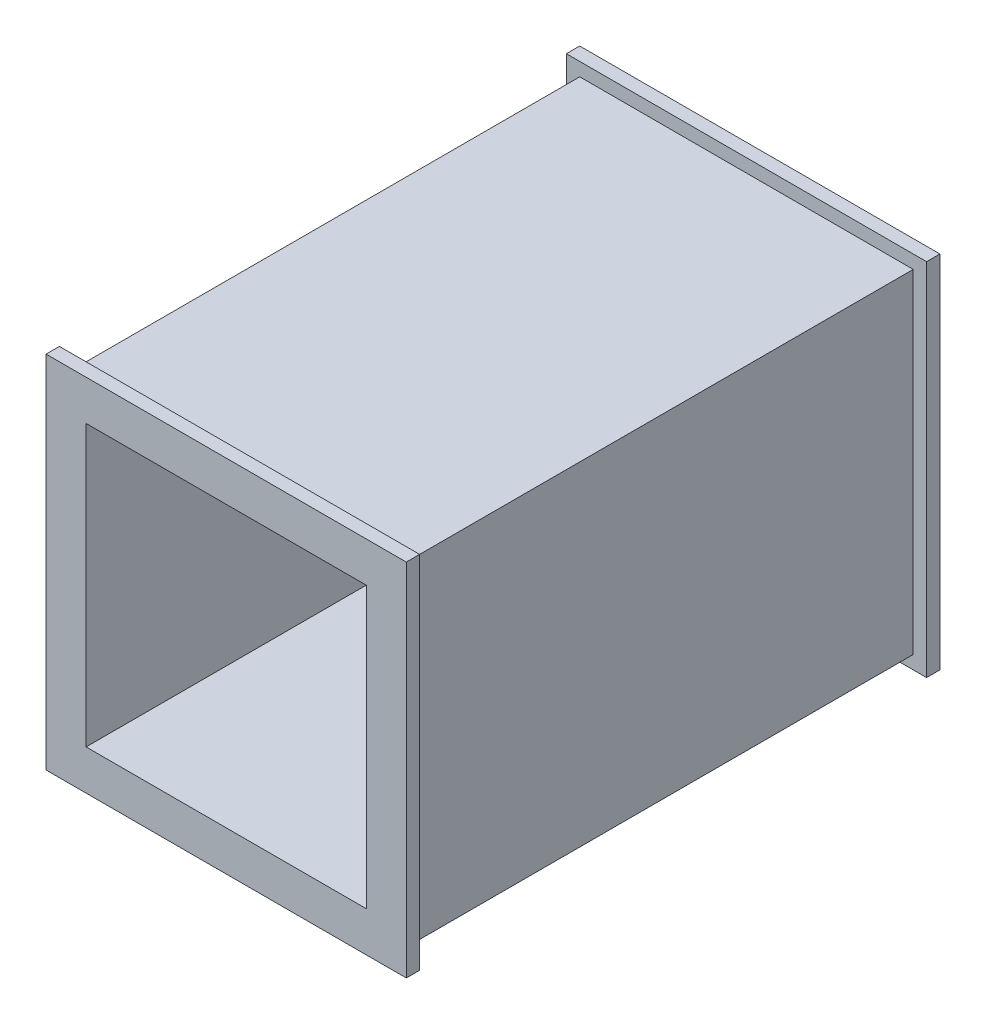
SolidWorks part; units mm, degrees
ref_plane "Front Plane" through (0, 0, 0) normal (0, 0, 1) x (1, 0, 0)
ref_plane "Top Plane" through (0, 0, 0) normal (0, 1, 0) x (1, 0, 0)
ref_plane "Right Plane" through (0, 0, 0) normal (1, 0, 0) x (0, 0, -1)
sketch "Sketch1" plane through (0, 0, 0) normal (0, 0, 1) x (1, 0, 0)
  line L1 (-62.5, 62.5) -> (62.5, 62.5)
  line L2 (-62.5, 62.5) -> (-62.5, -62.5)
  line L3 (-62.5, -62.5) -> (62.5, -62.5)
  line L4 (62.5, 62.5) -> (62.5, -62.5)
  line L5 (-62.5, 62.5) -> (62.5, -62.5) construction
  line L6 (-62.5, -62.5) -> (62.5, 62.5) construction
  point P0 (0, 0)
  dimension "D1" = 125
  dimension "D2" = 125
extrude "Boss-Extrude1" add sketch "Sketch1" along normal blind 200
shell "Shell1" thickness 10
sketch "Sketch2" plane through (0, 0, 200) normal (0, 0, 1) x (1, 0, 0)
  line L0 (67.5, 67.5) -> (-67.5, 67.5)
  line L1 (-67.5, 67.5) -> (-67.5, -67.5)
  line L2 (-67.5, -67.5) -> (67.5, -67.5)
  line L3 (67.5, -67.5) -> (67.5, 67.5)
  line L4 (62.5, -62.5) -> (62.5, 62.5)
  line L5 (62.5, 62.5) -> (-62.5, 62.5)
  line L6 (-62.5, 62.5) -> (-62.5, -62.5)
  line L7 (-62.5, -62.5) -> (62.5, -62.5)
  line L8 (62.5, -62.5) -> (62.5, 62.5)
  line L9 (62.5, 62.5) -> (-62.5, 62.5)
  line L10 (-62.5, 62.5) -> (-62.5, -62.5)
  line L11 (-62.5, -62.5) -> (62.5, -62.5)
  line M5 (52.5, 52.5) -> (52.5, -52.5)
  line M6 (52.5, -52.5) -> (-52.5, -52.5)
  line M7 (-52.5, -52.5) -> (-52.5, 52.5)
  line M8 (-52.5, 52.5) -> (52.5, 52.5)
  line M9 (62.5, -62.5) -> (62.5, 62.5)
  line M10 (62.5, 62.5) -> (-62.5, 62.5)
  line M11 (-62.5, 62.5) -> (-62.5, -62.5)
  line M12 (-62.5, -62.5) -> (62.5, -62.5)
  dimension "D1" = 0
  dimension "D2" = 5
extrude "Boss-Extrude2" add sketch "Sketch2" against normal blind 5 contours L2 L3 L0 L1 M9 M12 M11 M10 | M12 M9 M10 M11 M8 M5 M6 M7
sketch "Sketch3" plane through (0, 0, 0) normal (0, 0, -1) x (-1, 0, 0)
  line L0 (67.5, 67.5) -> (-67.5, 67.5)
  line L1 (-67.5, 67.5) -> (-67.5, -67.5)
  line L2 (-67.5, -67.5) -> (67.5, -67.5)
  line L3 (67.5, -67.5) -> (67.5, 67.5)
  line L4 (-62.5, 62.5) -> (-62.5, -62.5)
  line L5 (-62.5, -62.5) -> (62.5, -62.5)
  line L6 (62.5, -62.5) -> (62.5, 62.5)
  line L7 (62.5, 62.5) -> (-62.5, 62.5)
  line L8 (-62.5, 62.5) -> (-62.5, -62.5)
  line L9 (-62.5, -62.5) -> (62.5, -62.5)
  line L10 (62.5, -62.5) -> (62.5, 62.5)
  line L11 (62.5, 62.5) -> (-62.5, 62.5)
  line M5 (52.5, -52.5) -> (-52.5, -52.5)
  line M6 (-52.5, -52.5) -> (-52.5, 52.5)
  line M7 (-52.5, 52.5) -> (52.5, 52.5)
  line M8 (52.5, 52.5) -> (52.5, -52.5)
  line M9 (-62.5, 62.5) -> (-62.5, -62.5)
  line M10 (-62.5, -62.5) -> (62.5, -62.5)
  line M11 (62.5, -62.5) -> (62.5, 62.5)
  line M12 (62.5, 62.5) -> (-62.5, 62.5)
  dimension "D1" = 0
  dimension "D2" = 5
extrude "Boss-Extrude3" add sketch "Sketch3" against normal blind 5 contours L2 L3 L0 L1 M9 M12 M11 M10 | M12 M9 M10 M11 M8 M5 M6 M7
